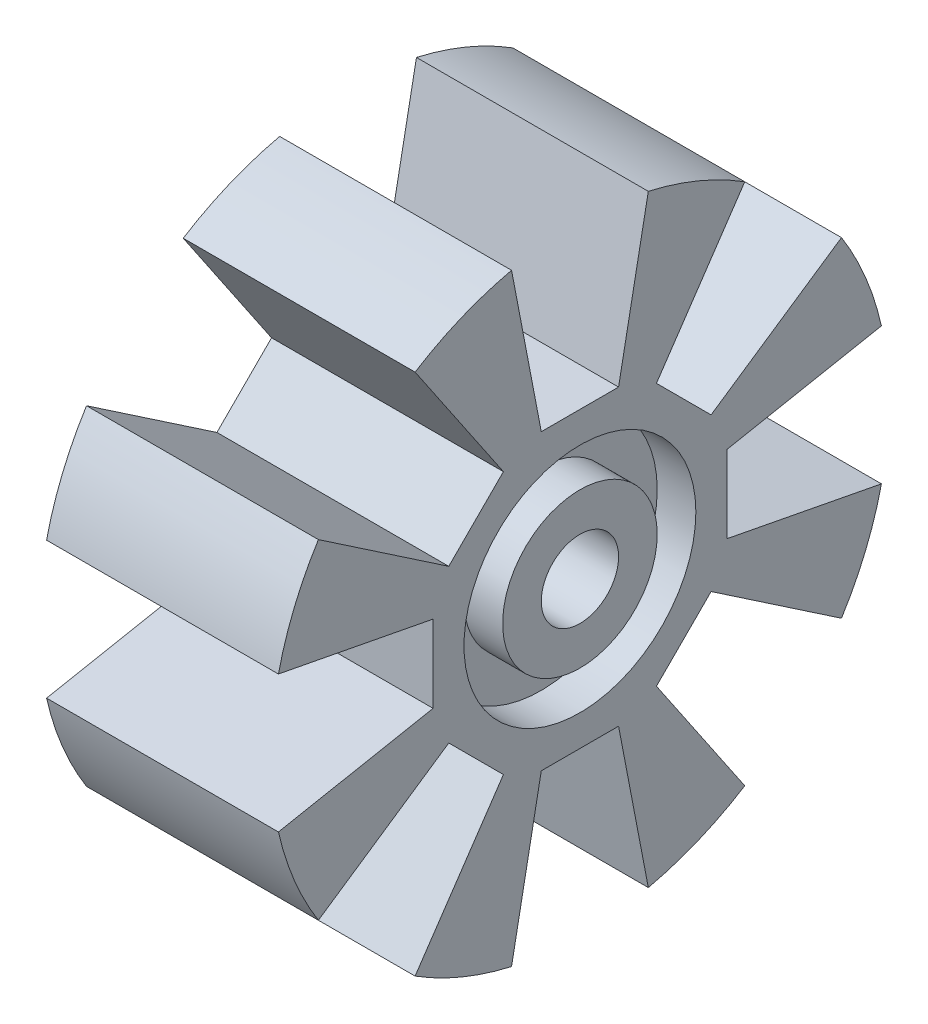
SolidWorks part; units mm, degrees
ref_plane "Front Plane" through (0, 0, 0) normal (0, 0, 1) x (1, 0, 0)
ref_plane "Top Plane" through (0, 0, 0) normal (0, 1, 0) x (1, 0, 0)
ref_plane "Right Plane" through (0, 0, 0) normal (1, 0, 0) x (0, 0, -1)
sketch "Sketch2" plane through (0, 0, 0) normal (0, 0, 1) x (1, 0, 0)
  line L0 (0, 0) -> (-19.0453, 0) construction
  line L1 (0, 5) -> (-30, 5)
  line L2 (-30, 5) -> (-30, 10)
  line L3 (-30, 10) -> (-25, 10)
  line L4 (-25, 10) -> (-25, 15)
  line L5 (-25, 15) -> (-30, 15)
  line L6 (-30, 15) -> (-30, 40)
  line L7 (-30, 40) -> (0, 40)
  line L8 (0, 40) -> (0, 15)
  line L9 (0, 15) -> (-5, 15)
  line L10 (-5, 15) -> (-5, 10)
  line L11 (-5, 10) -> (0, 10)
  line L12 (0, 10) -> (0, 5)
  point P19 (-25, 12.5)
  dimension "D1" = 10
  dimension "D2" = 80
  dimension "D3" = 30
  dimension "D4" = 5
  dimension "D5" = 20
  dimension "D6" = 25
revolve "Revolve1" add sketch "Sketch2" angle 360 about L0
sketch "Sketch8" plane through (-30, 0, 0) normal (-1, 0, 0) x (0, 0, 1)
  line L0 (-10, 45) -> (10, 45)
  line L1 (10, 45) -> (5, 19)
  line L2 (5, 19) -> (-5, 19)
  line L3 (-5, 19) -> (-10, 45)
  circle A0 centre (0, 0) radius 40 construction
  point P2 (0, 45)
  point P5 (0, 19)
  point P9 (0, 40)
  dimension "D1" = 26
  dimension "D2" = 10
  dimension "D3" = 20
  dimension "D4" = 5
extrude "Cut-Extrude6" cut sketch "Sketch8" against normal through all
pattern_circular "CirPattern6" count 8 over 360 about axis through (0, 0, 0) along (1, 0, 0) of "Cut-Extrude6"
